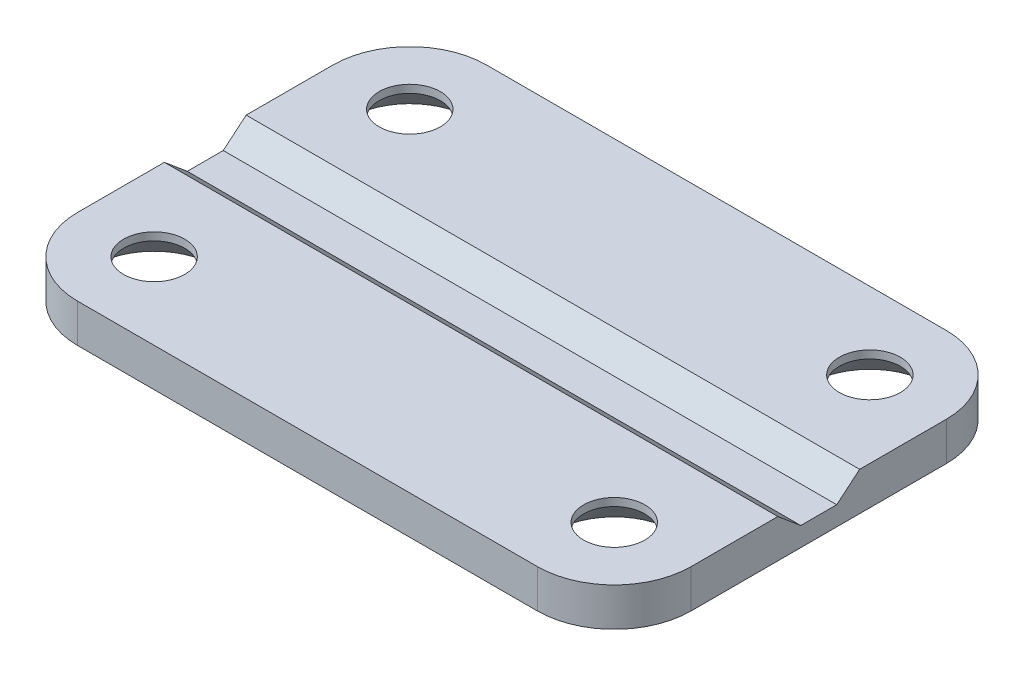
SolidWorks part; units mm, degrees
ref_plane "Front" through (0, 0, 0) normal (0, 0, 1) x (1, 0, 0)
ref_plane "Top" through (0, 0, 0) normal (0, 1, 0) x (1, 0, 0)
ref_plane "Right" through (0, 0, 0) normal (1, 0, 0) x (0, 0, -1)
sketch "Sketch2" plane through (0, 0, 0) normal (1, 0, 0) x (0, 0, -1)
  line L0 (-12.7, 2.3876) -> (-2.54, 2.3876)
  line L1 (-12.7, 0) -> (12.7, 0)
  line L2 (-12.7, 0) -> (-12.7, 2.3876)
  line L3 (-12.7, 2.3876) -> (12.7, 2.3876) construction
  line L4 (12.7, 0) -> (12.7, 2.3876)
  line L5 (-2.54, 2.3876) -> (-1.1173, 1.1938)
  line L6 (-12.7, 1.1938) -> (12.7, 1.1938) construction
  line L7 (-1.1173, 1.1938) -> (1.1173, 1.1938)
  line L8 (2.54, 2.3876) -> (12.7, 2.3876)
  line L9 (1.1173, 1.1938) -> (2.54, 2.3876)
  line L10 (0, 0) -> (0, 1.1938) construction
  point P8 (0, 1.1938)
  point P14 (-7.9375, 2.3876)
  point P15 (7.9375, 2.3876)
  point P16 (-3.175, 2.3876)
  dimension "D1" = 1.1938
  dimension "Open Width" = 25.4
  dimension "Thickness" = 2.3876
  dimension "D2" = 6.35
  dimension "D3" = 7.9375
  dimension "D4" = 15.875
  dimension "D5" = 4.7625
  dimension "D6" = 4.7625
  dimension "D7" = 5.08
  dimension "D8" = 40
extrude "Extrude1" add sketch "Sketch2" along normal mid plane 38.1
sketch "Sketch3" plane through (0, 2.3876, 0) normal (0, 1, 0) x (-1, 0, 0)
  line L0 (0, -12.7) -> (0, 12.7) construction
  line L1 (-19.05, -12.7) -> (19.05, -12.7) construction
  line L2 (-19.05, 12.7) -> (19.05, 12.7) construction
  line L3 (19.05, 0) -> (-19.05, 0) construction
  line L6 (-19.05, 2.54) -> (-19.05, 12.7) construction
  line L7 (19.05, -12.7) -> (19.05, -2.54) construction
  point P0 (14.2875, -7.9375)
  point P1 (-14.2875, -7.9375)
  point P2 (-14.2875, 7.9375)
  point P3 (14.2875, 7.9375)
  dimension "D1" = 4.7625
  dimension "Hole Dist" = 28.575
  dimension "hole center" = 15.875
hole_wizard "CSK for #5 Flat Head Machine Screw1" positions "3DSketch1" profile "Sketch4" countersink size "#5" standard "Ansi Inch"
sketch3d "3DSketch1"
  point P0 (-16.6687, 3.175, 11.1125)
  point P6 (-16.6687, 3.175, -11.1125)
  point P9 (16.6687, 3.175, -11.1125)
  point P12 (16.6687, 3.175, 11.1125)
sketch "Sketch4" plane through (-16.6687, 3.175, 11.1125) normal (1, 0, 0) x (0, 0, 1)
  line L0 (0, 0) -> (0, 3.175)
  line L1 (0, 3.175) -> (1.7272, 3.175)
  line L2 (1.7272, 3.175) -> (1.7272, 1.6947)
  line L3 (1.7272, 1.6947) -> (3.2004, 0)
  line L5 (3.2004, 0) -> (0, 0)
  line L6 (-1.7272, 1.6947) -> (-3.2004, 0) construction
  line L11 (0, -6.35) -> (0, 107.95) construction
  dimension "Thru Hole Dia." = 3.4544
  dimension "Thru Hole Depth" = 3.175
  dimension "Near C'Sink Dia." = 6.4008
  dimension "Near C'Sink Angle" = 82
hole_wizard "CSK for #6 Flat Head Machine Screw1" positions "3DSketch2" profile "Sketch5" countersink size "#6" standard "Ansi Inch" end condition through all
sketch3d "3DSketch2"
  point P0 (-14.2875, 2.3876, 7.9375)
  point P5 (14.2875, 2.3876, -7.9375)
  point P8 (14.2875, 2.3876, 7.9375)
  point P13 (-14.2875, 2.3876, -7.9375)
sketch "Sketch5" plane through (-14.2875, 2.3876, 7.9375) normal (1, 0, 0) x (0, 0, 1)
  line L0 (0, 0) -> (0, 2.3876)
  line L1 (0, 2.3876) -> (1.8986, 2.3876)
  line L2 (1.8986, 2.3876) -> (1.8986, 1.892)
  line L3 (1.8986, 1.892) -> (3.5433, 0)
  line L5 (3.5433, 0) -> (0, 0)
  line L6 (-1.8986, 1.892) -> (-3.5433, 0) construction
  line L11 (0, -6.35) -> (0, 107.95) construction
  dimension "Thru Hole Dia." = 3.7973
  dimension "Thru Hole Depth" = 2.3876
  dimension "Near C'Sink Dia." = 7.0866
  dimension "Near C'Sink Angle" = 82
fillet "Fillet1" radius 4.7752 4 edges at (19.05, 1.1938, -12.7) (19.05, 1.1938, 12.7) (-19.05, 1.1938, -12.7) (-19.05, 1.1938, 12.7)
sketch "Sketch6" plane through (0, 2.3876, 0) normal (0, 1, 0) x (1, 0, 0)
  circle A0 centre (-14.2875, -7.9375) radius 3.5433 construction
  circle A1 centre (-14.2875, 7.9375) radius 3.5433 construction
  circle A2 centre (14.2875, -7.9375) radius 3.5433 construction
  circle A3 centre (14.2875, 7.9375) radius 3.5433 construction
  circle A4 centre (-14.2875, 7.9375) radius 1.8986 construction
  circle A5 centre (-14.2875, -7.9375) radius 1.8986 construction
  circle A6 centre (14.2875, -7.9375) radius 1.8986 construction
  circle A7 centre (14.2875, 7.9375) radius 1.8986 construction
  circle A8 centre (-14.2875, -7.9375) radius 3.5433
  circle A9 centre (-14.2875, 7.9375) radius 3.5433
  circle A10 centre (14.2875, -7.9375) radius 3.5433
  circle A11 centre (14.2875, 7.9375) radius 3.5433
  circle A12 centre (-14.2875, 7.9375) radius 1.8986
  circle A13 centre (-14.2875, -7.9375) radius 1.8986
  circle A14 centre (14.2875, -7.9375) radius 1.8987
  circle A15 centre (14.2875, 7.9375) radius 1.8987
extrude "Boss-Extrude1" add sketch "Sketch6" against normal up to surface (2.3876 mm away) up to face at (-14.2875, 0, 9.8361)
chamfer "Chamfer1" distance 1.8986 angle 45 4 edges at (-14.2875, 0, -6.0389) (14.2875, 0, -6.0389) (14.2875, 0, 9.8361) (-14.2875, 0, 9.8361)
equation "\"D3@Sketch2\" = \"hole center@Sketch3\"/2"
equation "\"D4@Sketch2\" = \"hole center@Sketch3\""
equation "\"D6@Sketch2\" = \"D5@Sketch2\""
equation "\"D1@Sketch2\" = \"Thickness@Sketch2\"/2"
equation "\"D7@Sketch2\" = \"D2@Sketch2\"*.8"
equation "\"D1@Fillet1\" = \"Thickness@Sketch2\"*2"
equation "\"D1@Chamfer1\" = \"Thru Hole Dia.@Sketch5\" * .5"
